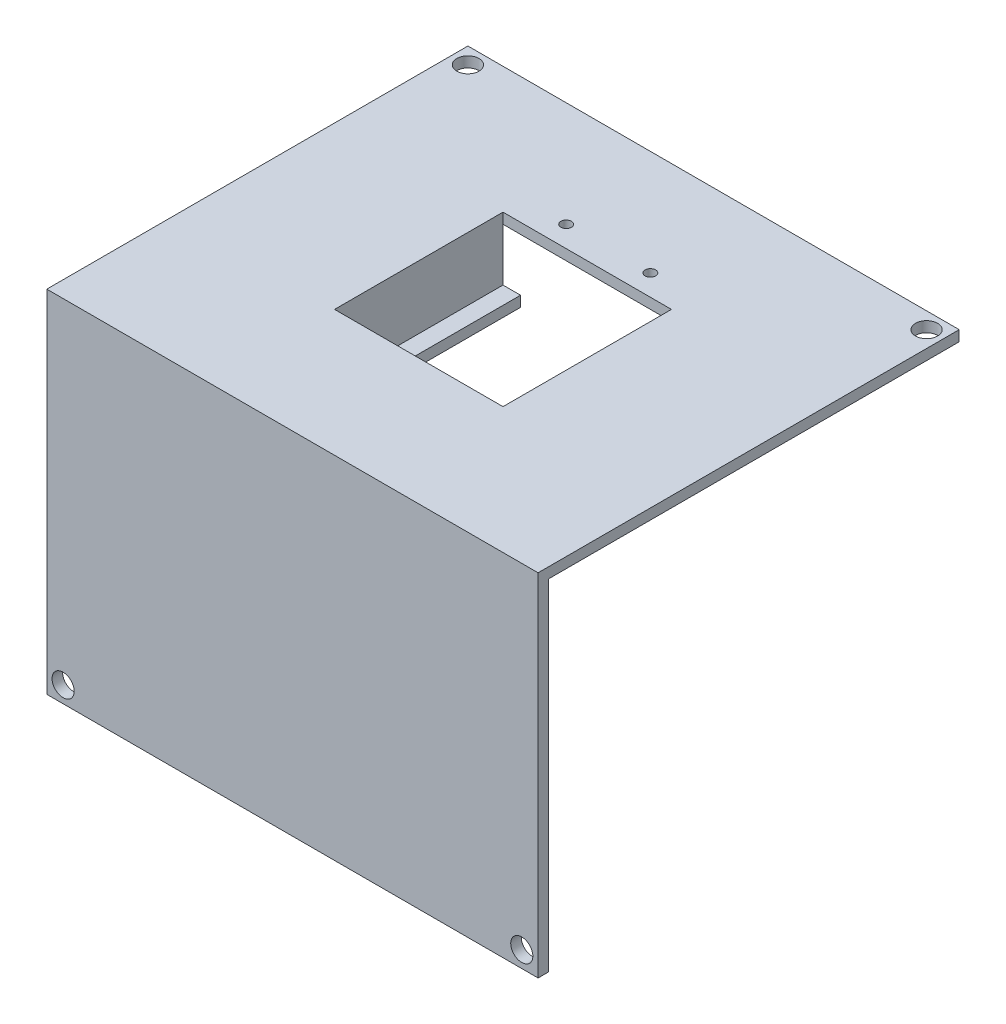
SolidWorks part; units mm, degrees
ref_plane "Front Plane" through (0, 0, 0) normal (0, 0, 1) x (1, 0, 0)
ref_plane "Top Plane" through (0, 0, 0) normal (0, 1, 0) x (1, 0, 0)
ref_plane "Right Plane" through (0, 0, 0) normal (1, 0, 0) x (0, 0, -1)
sketch "Sketch1" plane through (0, 0, 0) normal (0, 1, 0) x (1, 0, 0)
  line L1 (-70, 60) -> (70, 60)
  line L2 (-70, 60) -> (-70, -60)
  line L3 (-70, -60) -> (70, -60)
  line L4 (70, 60) -> (70, -60)
  line L5 (-70, 60) -> (70, -60) construction
  line L6 (-70, -60) -> (70, 60) construction
  point P0 (0, 0)
  dimension "D1" = 120
  dimension "D2" = 140
extrude "Boss-Extrude1" add sketch "Sketch1" along normal blind 100
sketch "Sketch2" plane through (0, 100, 0) normal (0, 1, 0) x (1, 0, 0)
  line L0 (-70, 60) -> (-70, -60) construction
  line L1 (70, 60) -> (-70, 60) construction
  line L2 (70, -60) -> (70, 60) construction
  point P0 (-65.35, 55.35)
  point P1 (65.35, 55.35)
  dimension "D1" = 4.65
  dimension "D2" = 4.65
  dimension "D3" = 4.65
sketch "Sketch4" plane through (0, 0, 60) normal (0, 0, 1) x (1, 0, 0)
  line L0 (-70, 100) -> (-70, 0) construction
  line L1 (-70, 0) -> (70, 0) construction
  line L2 (70, 100) -> (70, 0) construction
  point P0 (-65.35, 4.65)
  point P1 (65.35, 4.65)
  dimension "D1" = 4.65
  dimension "D2" = 4.65
  dimension "D3" = 4.65
sketch "Sketch6" plane through (0, 0, 60) normal (0, 0, 1) x (1, 0, 0)
  circle A0 centre (-65.35, 4.65) radius 3.15
  circle A1 centre (65.35, 4.65) radius 3.15
  dimension "D1" = 6.3
  dimension "D2" = 6.3
sketch "Sketch7" plane through (0, 100, 0) normal (0, 1, 0) x (1, 0, 0)
  circle A0 centre (-65.35, 55.35) radius 3.15
  circle A1 centre (65.35, 55.35) radius 3.15
shell "Shell1" thickness 3
extrude "Cut-Extrude4" cut sketch "Sketch6" against normal blind 3 contours A1 | A0
extrude "Cut-Extrude5" cut sketch "Sketch7" against normal blind 3 contours A1 | A0
sketch "Sketch8" plane through (0, 97, 0) normal (0, -1, 0) x (1, 0, 0)
  line L1 (-24, -24) -> (24, -24)
  line L2 (-24, -24) -> (-24, 24)
  line L3 (-24, 24) -> (24, 24)
  line L4 (24, -24) -> (24, 24)
  line L5 (-24, -24) -> (24, 24) construction
  line L6 (-24, 24) -> (24, -24) construction
  point P0 (0, 0)
  dimension "D1" = 48
  dimension "D2" = 48
extrude "Cut-Extrude6" cut sketch "Sketch8" against normal blind 3
sketch "Sketch9" plane through (0, 97, 0) normal (0, -1, 0) x (1, 0, 0)
  line L0 (24, -24) -> (24, 24)
  line L1 (24, 24) -> (29, 24)
  line L2 (29, 24) -> (29, -24)
  line L3 (29, -24) -> (24, -24)
  line L4 (0, 0) -> (0, 46.757) construction
  line L5 (-29, 24) -> (-29, -24)
  line L6 (-24, 24) -> (-29, 24)
  line L7 (-24, -24) -> (-24, 24)
  line L8 (-29, -24) -> (-24, -24)
  dimension "D1" = 5
extrude "Boss-Extrude2" add sketch "Sketch9" along normal blind 15
sketch "Sketch10" plane through (0, 82, 0) normal (0, -1, 0) x (1, 0, 0)
  line L0 (29, -24) -> (29, 24)
  line L1 (29, 24) -> (19, 24)
  line L2 (24, 24) -> (-24, 24) construction
  line L3 (19, 24) -> (19, -24)
  line L4 (-24, -24) -> (24, -24) construction
  line L5 (19, -24) -> (29, -24)
  line L6 (0, 0) -> (0, 40.9048) construction
  line L7 (-19, 24) -> (-19, -24)
  line L8 (-29, 24) -> (-19, 24)
  line L9 (-29, -24) -> (-29, 24)
  line L10 (-19, -24) -> (-29, -24)
  dimension "D1" = 10
extrude "Boss-Extrude3" add sketch "Sketch10" along normal blind 3
sketch "Sketch11" plane through (0, 97, 0) normal (0, -1, 0) x (1, 0, 0)
  line L0 (0, 0) -> (0, -79.8618) construction
  point P0 (-12, -30)
  point P4 (0, 0)
  point P5 (12, -30)
  dimension "D1" = 12
  dimension "D2" = 30
hole_wizard "Ø3.0mm Dowel Hole1" positions "Sketch12" profile "Sketch13" hole size "Ø3.0" standard "ANSI Metric"
sketch "Sketch12" plane through (0, 97, 0) normal (0, -1, 0) x (-1, 0, 0)
  point P0 (12, 30)
  point P3 (-12, 30)
sketch "Sketch13" plane through (-12, 97, -30) normal (1, 0, 0) x (0, 0, -1)
  line L0 (0, 0) -> (0, 5.9013)
  line L1 (0, 5.9013) -> (1.5, 5)
  line L2 (1.5, 5) -> (1.5, 0)
  line L5 (1.5, 0) -> (0, 0)
  line L10 (0, 5.9013) -> (-1.5, 5) construction
  line L11 (0, -6.35) -> (0, 107.95) construction
  dimension "Hole Dia." = 3
  dimension "Hole Depth" = 5
  dimension "Drill Angle" = 118
